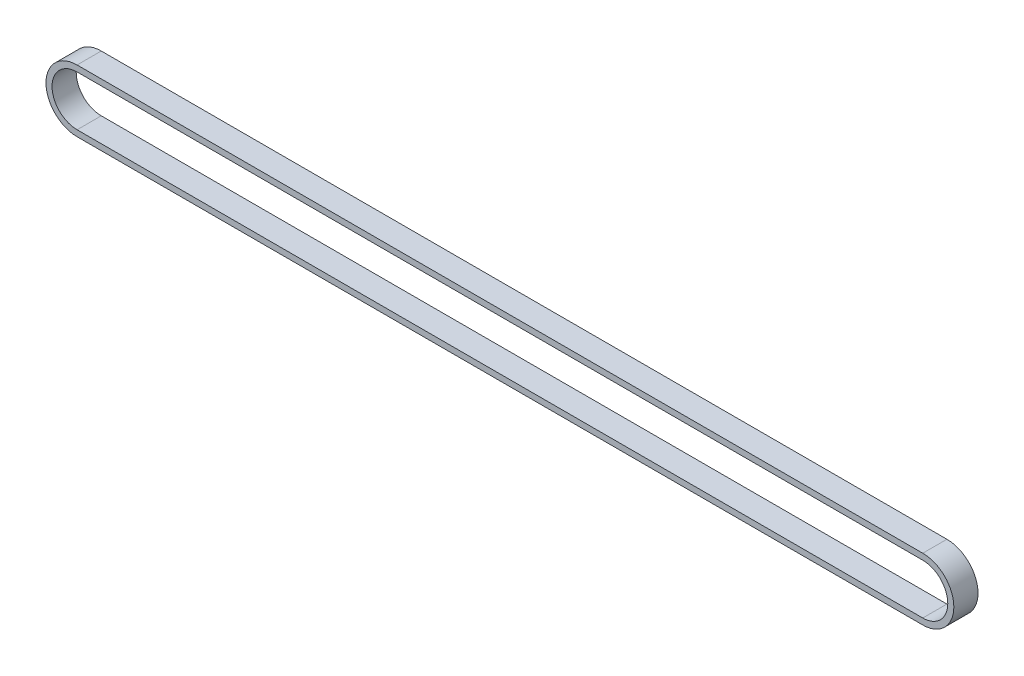
SolidWorks part; units mm, degrees
ref_plane "Front Plane" through (0, 0, 0) normal (0, 0, 1) x (1, 0, 0)
ref_plane "Top Plane" through (0, 0, 0) normal (0, 1, 0) x (1, 0, 0)
ref_plane "Right Plane" through (0, 0, 0) normal (1, 0, 0) x (0, 0, -1)
sketch "Sketch1" plane through (0, 0, 0) normal (0, 0, 1) x (1, 0, 0)
  line L0 (0, 0) -> (210, 0) construction
  line L1 (0, 6.215) -> (210, 6.215)
  line L2 (0, -6.215) -> (210, -6.215)
  line L3 (0, 0) -> (210, 0) construction
  line L4 (0, 7.72) -> (210, 7.72)
  line L5 (0, -7.72) -> (210, -7.72)
  arc A0 (0, 6.215) -> (0, -6.215) centre (0, 0) ccw
  arc A1 (210, -6.215) -> (210, 6.215) centre (210, 0) ccw
  arc A2 (0, 7.72) -> (0, -7.72) centre (0, 0) ccw
  arc A3 (210, -7.72) -> (210, 7.72) centre (210, 0) ccw
  point P3 (105, 0)
  point P10 (105, 0)
  dimension "D3" = 7.72
  dimension "D1" = 210
  dimension "D2" = 6.215
extrude "Boss-Extrude1" add sketch "Sketch1" along normal blind 6
